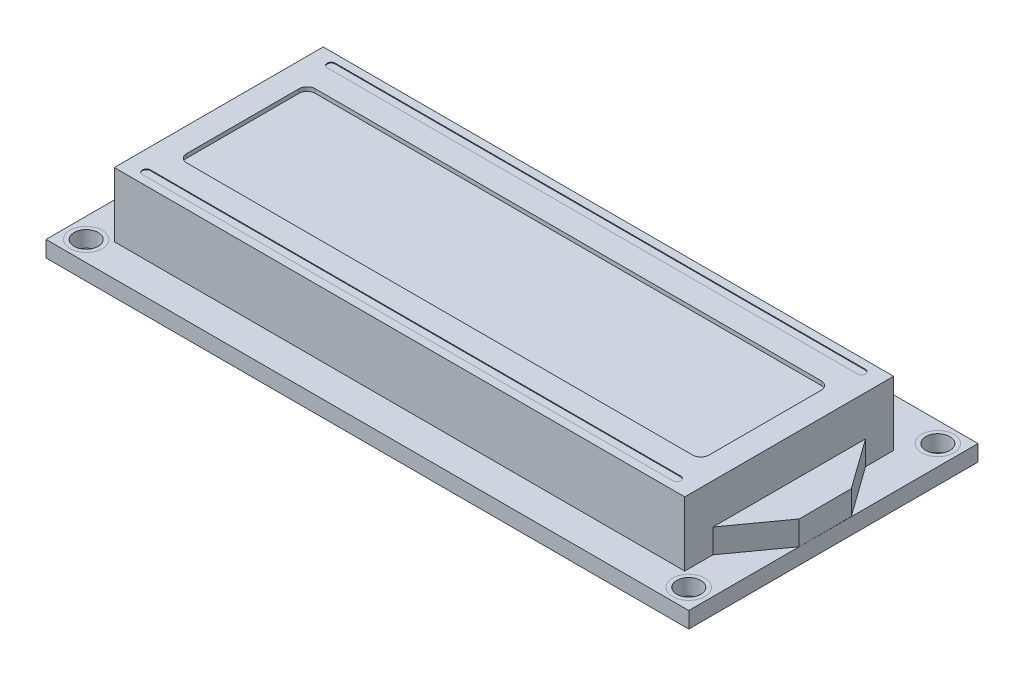
SolidWorks part; units mm, degrees
ref_plane "Front Plane" through (0, 0, 0) normal (0, 0, 1) x (1, 0, 0)
ref_plane "Top Plane" through (0, 0, 0) normal (0, 1, 0) x (1, 0, 0)
ref_plane "Right Plane" through (0, 0, 0) normal (1, 0, 0) x (0, 0, -1)
sketch "Sketch1" plane through (0, 0, 0) normal (0, 1, 0) x (1, 0, 0)
  line L1 (40, 18) -> (-40, 18)
  line L2 (40, 18) -> (40, -18)
  line L3 (40, -18) -> (-40, -18)
  line L4 (-40, 18) -> (-40, -18)
  line L5 (40, 18) -> (-40, -18) construction
  line L6 (40, -18) -> (-40, 18) construction
  point P0 (0, 0)
  dimension "D1" = 80
  dimension "D2" = 36
extrude "Boss-Extrude1" add sketch "Sketch1" along normal blind 2
sketch "Sketch2" plane through (0, 2, 0) normal (0, 1, 0) x (1, 0, 0)
  line L0 (-40, 18) -> (-40, 15.5)
  line L1 (-40, 18) -> (-40, -18) construction
  line L2 (-40, 15.5) -> (-37.5, 15.5)
  line L3 (0, 0) -> (0, 50000) construction
  line L4 (0, 0) -> (50000, 0) construction
  circle A0 centre (-37.5, 15.5) radius 1.5
  circle A1 centre (37.5, 15.5) radius 1.5
  circle A2 centre (-37.5, -15.5) radius 1.5
  circle A3 centre (37.5, -15.5) radius 1.5
  dimension "D3" = 3
  dimension "D1" = 2.5
  dimension "D2" = 2.5
extrude "Cut-Extrude1" cut sketch "Sketch2" against normal through all contours A2 | A0 | A1 | A3
sketch "Sketch3" plane through (0, 2, 0) normal (0, 1, 0) x (1, 0, 0)
  line L0 (0, -18) -> (0, -14) construction
  line L1 (-40, -18) -> (40, -18) construction
  line L2 (0, 18) -> (0, 12) construction
  line L3 (40, 18) -> (-40, 18) construction
  line L4 (-40, 0) -> (-35.5, 0) construction
  line L5 (-40, 18) -> (-40, -18) construction
  line L6 (40, 0) -> (35.5, 0) construction
  line L7 (40, -18) -> (40, 18) construction
  line L8 (-35.5, -1.0136) -> (-35.5, -50001.0136) construction
  line L9 (0, -14) -> (50000, -14) construction
  line L10 (35.5, 0) -> (35.5, -50000) construction
  line L11 (0, 12) -> (50000, 12) construction
  line L13 (-35.5, 12) -> (35.5, 12)
  line L14 (-35.5, 12) -> (-35.5, -14)
  line L15 (-35.5, -14) -> (35.5, -14)
  line L16 (35.5, 12) -> (35.5, -14)
  dimension "D1" = 4.5
  dimension "D2" = 4
  dimension "D3" = 6
extrude "Boss-Extrude2" add sketch "Sketch3" along normal blind 8 contours L14 L15 L16 L13
sketch "Sketch5" plane through (0, 10, 0) normal (0, 1, 0) x (1, 0, 0)
  line L4 (0, 12) -> (0, 7) construction
  line L5 (-35.5, 12) -> (35.5, 12) construction
  line L6 (-35.5, -1) -> (-32.5, -1) construction
  line L7 (-35.5, 12) -> (-35.5, -14) construction
  line L8 (35.5, -1) -> (32.5, -1) construction
  line L9 (35.5, 12) -> (35.5, -14) construction
  line L10 (0, -14) -> (0, -9) construction
  line L11 (-35.5, -14) -> (35.5, -14) construction
  line L12 (-32.5, -1) -> (-32.5, -50001) construction
  line L13 (0.9619, 7) -> (50000.9619, 7) construction
  line L14 (32.5, -1) -> (32.5, -50001) construction
  line L15 (0, -9) -> (50000, -9) construction
  line L17 (-31.5, 7) -> (31.5, 7)
  line L18 (-32.5, 6) -> (-32.5, -8)
  line L19 (-31.5, -9) -> (31.5, -9)
  line L20 (32.5, 6) -> (32.5, -8)
  arc A0 (31.5, -9) -> (32.5, -8) centre (31.5, -8) ccw
  arc A1 (32.5, 6) -> (31.5, 7) centre (31.5, 6) ccw
  arc A2 (-31.5, 7) -> (-32.5, 6) centre (-31.5, 6) ccw
  arc A3 (-32.5, -8) -> (-31.5, -9) centre (-31.5, -8) ccw
  point P31 (32.5, -9)
  point P36 (-32.5, 7)
  dimension "D3" = 1
  dimension "D1" = 3
  dimension "D2" = 5
extrude "Cut-Extrude2" cut sketch "Sketch5" against normal blind 0.5
sketch "Sketch6" plane through (0, 10, 0) normal (0, 1, 0) x (1, 0, 0)
  line L0 (-35.5, 12) -> (-35.5, 11) construction
  line L1 (-35.5, 12) -> (-35.5, -14) construction
  line L2 (-35.5, 11) -> (-35.5, 10) construction
  line L3 (-35.5, 12) -> (-35.5, -14) construction
  line L4 (-35.5, 10) -> (49964.5, 10) construction
  line L5 (-35.5, 11) -> (49964.5, 11) construction
  line L6 (-35.5, 12) -> (-33.5, 12) construction
  line L7 (-35.5, 12) -> (35.5, 12) construction
  line L8 (-33.5, 12) -> (-33.5, 10) construction
  line L9 (35.5, 12) -> (33.5, 12) construction
  line L10 (33.5, 12) -> (33.5, 10) construction
  line L11 (-32.5, -1) -> (49967.5, -1) construction
  line L12 (33.01, 10) -> (-33.01, 10)
  line L13 (33.5, 10.49) -> (33.5, 10.51)
  line L14 (33.01, 11) -> (-33.01, 11)
  line L15 (-33.5, 10.49) -> (-33.5, 10.51)
  line L16 (-32.5, 6) -> (-32.5, -8) construction
  line L17 (33.5, -14) -> (33.5, -12) construction
  line L18 (35.5, -14) -> (33.5, -14) construction
  line L19 (-33.5, -14) -> (-33.5, -12) construction
  line L20 (-35.5, -14) -> (-33.5, -14) construction
  line L21 (-35.5, -13) -> (49964.5, -13) construction
  line L22 (-35.5, -12) -> (49964.5, -12) construction
  line L23 (-35.5, -13) -> (-35.5, -12) construction
  line L24 (-35.5, -14) -> (-35.5, -13) construction
  line L25 (-33.5, -12.49) -> (-33.5, -12.51)
  line L26 (33.01, -13) -> (-33.01, -13)
  line L27 (33.5, -12.49) -> (33.5, -12.51)
  line L28 (33.01, -12) -> (-33.01, -12)
  arc A0 (33.5, 10.51) -> (33.01, 11) centre (33.01, 10.51) ccw
  arc A1 (33.5, 10.49) -> (33.01, 10) centre (33.01, 10.49) cw
  arc A2 (-33.5, 10.51) -> (-33.01, 11) centre (-33.01, 10.51) cw
  arc A3 (-33.5, 10.49) -> (-33.01, 10) centre (-33.01, 10.49) ccw
  arc A4 (-33.5, -12.49) -> (-33.01, -12) centre (-33.01, -12.49) cw
  arc A5 (-33.5, -12.51) -> (-33.01, -13) centre (-33.01, -12.51) ccw
  arc A6 (33.5, -12.49) -> (33.01, -12) centre (33.01, -12.49) ccw
  arc A7 (33.5, -12.51) -> (33.01, -13) centre (33.01, -12.51) cw
  point P29 (-33.5, 11)
  point P37 (-32.5, -1)
  point P62 (-33.5, -13)
  dimension "D5" = 0.49
  dimension "D1" = 1
  dimension "D2" = 1
  dimension "D3" = 2
  dimension "D4" = 2
extrude "Cut-Extrude3" cut sketch "Sketch6" against normal blind 0.1
sketch "Sketch7" plane through (0, 2, 0) normal (0, 1, 0) x (1, 0, 0)
  line L0 (35.5, 8.5) -> (35.5, -10.5)
  line L1 (35.5, 12) -> (35.5, -14) construction
  line L3 (35.5, -1) -> (39.99, -1) construction
  line L4 (39.98, 2.25) -> (40, -4.25)
  line L5 (40, -18) -> (40, 18) construction
  line L6 (35.5, 8.5) -> (39.98, 2.25)
  line L7 (40, -4.25) -> (35.5, -10.5)
  point P5 (35.5, -1)
  point P12 (39.99, -1)
  dimension "D1" = 19
  dimension "D2" = 4.49
  dimension "D3" = 6.5
extrude "Boss-Extrude3" add sketch "Sketch7" along normal blind 3
sketch "Sketch8" plane through (0, 2, 0) normal (0, 1, 0) x (1, 0, 0)
  line L0 (0, 0) -> (-50000, 0) construction
  line L1 (0, 0) -> (0, 50000) construction
  line L2 (-40, 18) -> (-33, 18) construction
  line L3 (40, 18) -> (-40, 18) construction
  line L4 (-32, 18) -> (-32, 16) construction
  line L5 (-33, 18) -> (-31, 18)
  line L6 (-33, 18) -> (-33, 16)
  line L7 (-30.5, 18) -> (-28.5, 18)
  line L8 (-31, 18) -> (-31, 16)
  line L9 (-32, 15) -> (-32, 16) construction
  line L10 (-30.5, 18) -> (-30.5, 16)
  line L11 (-28.5, 18) -> (-28.5, 16)
  line L12 (-29.5, 18) -> (-29.5, 16) construction
  line L13 (-29.5, 15) -> (-29.5, 16) construction
  line L14 (-28, 18) -> (-26, 18)
  line L15 (-28, 18) -> (-28, 16)
  line L16 (-26, 18) -> (-26, 16)
  line L17 (-27, 18) -> (-27, 16) construction
  line L18 (-27, 15) -> (-27, 16) construction
  line L19 (-25.5, 18) -> (-23.5, 18)
  line L20 (-25.5, 18) -> (-25.5, 16)
  line L21 (-23.5, 18) -> (-23.5, 16)
  line L22 (-24.5, 18) -> (-24.5, 16) construction
  line L23 (-24.5, 15) -> (-24.5, 16) construction
  line L24 (-23, 18) -> (-21, 18)
  line L25 (-23, 18) -> (-23, 16)
  line L26 (-21, 18) -> (-21, 16)
  line L27 (-22, 18) -> (-22, 16) construction
  line L28 (-22, 15) -> (-22, 16) construction
  line L29 (-20.5, 18) -> (-18.5, 18)
  line L30 (-20.5, 18) -> (-20.5, 16)
  line L31 (-18.5, 18) -> (-18.5, 16)
  line L32 (-19.5, 18) -> (-19.5, 16) construction
  line L33 (-19.5, 15) -> (-19.5, 16) construction
  line L34 (-18, 18) -> (-16, 18)
  line L35 (-18, 18) -> (-18, 16)
  line L36 (-16, 18) -> (-16, 16)
  line L37 (-17, 18) -> (-17, 16) construction
  line L38 (-17, 15) -> (-17, 16) construction
  line L39 (-15.5, 18) -> (-13.5, 18)
  line L40 (-15.5, 18) -> (-15.5, 16)
  line L41 (-13.5, 18) -> (-13.5, 16)
  line L42 (-14.5, 18) -> (-14.5, 16) construction
  line L43 (-14.5, 15) -> (-14.5, 16) construction
  line L44 (-13, 18) -> (-11, 18)
  line L45 (-13, 18) -> (-13, 16)
  line L46 (-11, 18) -> (-11, 16)
  line L47 (-12, 18) -> (-12, 16) construction
  line L48 (-12, 15) -> (-12, 16) construction
  line L49 (-10.5, 18) -> (-8.5, 18)
  line L50 (-10.5, 18) -> (-10.5, 16)
  line L51 (-8.5, 18) -> (-8.5, 16)
  line L52 (-9.5, 18) -> (-9.5, 16) construction
  line L53 (-9.5, 15) -> (-9.5, 16) construction
  line L54 (-8, 18) -> (-6, 18)
  line L55 (-8, 18) -> (-8, 16)
  line L56 (-6, 18) -> (-6, 16)
  line L57 (-7, 18) -> (-7, 16) construction
  line L58 (-7, 15) -> (-7, 16) construction
  line L59 (-5.5, 18) -> (-3.5, 18)
  line L60 (-5.5, 18) -> (-5.5, 16)
  line L61 (-3.5, 18) -> (-3.5, 16)
  line L62 (-4.5, 18) -> (-4.5, 16) construction
  line L63 (-4.5, 15) -> (-4.5, 16) construction
  line L64 (-3, 18) -> (-1, 18)
  line L65 (-3, 18) -> (-3, 16)
  line L66 (-1, 18) -> (-1, 16)
  line L67 (-2, 18) -> (-2, 16) construction
  line L68 (-2, 15) -> (-2, 16) construction
  line L69 (-0.5, 18) -> (1.5, 18)
  line L70 (-0.5, 18) -> (-0.5, 16)
  line L71 (1.5, 18) -> (1.5, 16)
  line L72 (0.5, 18) -> (0.5, 16) construction
  line L73 (0.5, 15) -> (0.5, 16) construction
  line L74 (2, 18) -> (4, 18)
  line L75 (2, 18) -> (2, 16)
  line L76 (4, 18) -> (4, 16)
  line L77 (3, 18) -> (3, 16) construction
  line L78 (3, 15) -> (3, 16) construction
  line L79 (4.5, 18) -> (6.5, 18)
  line L80 (4.5, 18) -> (4.5, 16)
  line L81 (6.5, 18) -> (6.5, 16)
  line L82 (5.5, 18) -> (5.5, 16) construction
  line L83 (5.5, 15) -> (5.5, 16) construction
  circle A0 centre (-37.5, 15.5) radius 2
  circle A1 centre (37.5, 15.5) radius 2
  circle A2 centre (37.5, -15.5) radius 2
  circle A3 centre (-37.5, -15.5) radius 2
  arc A4 (-33, 16) -> (-31, 16) centre (-32, 16) ccw
  arc A5 (-30.5, 16) -> (-28.5, 16) centre (-29.5, 16) ccw
  arc A6 (-28, 16) -> (-26, 16) centre (-27, 16) ccw
  arc A7 (-25.5, 16) -> (-23.5, 16) centre (-24.5, 16) ccw
  arc A8 (-23, 16) -> (-21, 16) centre (-22, 16) ccw
  arc A9 (-20.5, 16) -> (-18.5, 16) centre (-19.5, 16) ccw
  arc A10 (-18, 16) -> (-16, 16) centre (-17, 16) ccw
  arc A11 (-15.5, 16) -> (-13.5, 16) centre (-14.5, 16) ccw
  arc A12 (-13, 16) -> (-11, 16) centre (-12, 16) ccw
  arc A13 (-10.5, 16) -> (-8.5, 16) centre (-9.5, 16) ccw
  arc A14 (-8, 16) -> (-6, 16) centre (-7, 16) ccw
  arc A15 (-5.5, 16) -> (-3.5, 16) centre (-4.5, 16) ccw
  arc A16 (-3, 16) -> (-1, 16) centre (-2, 16) ccw
  arc A17 (-0.5, 16) -> (1.5, 16) centre (0.5, 16) ccw
  arc A18 (2, 16) -> (4, 16) centre (3, 16) ccw
  arc A19 (4.5, 16) -> (6.5, 16) centre (5.5, 16) ccw
  dimension "D1" = 4
  dimension "D2" = 7
  dimension "D3" = 16
split line "Split Line1"
sketch "Sketch10" plane through (0, 2, 0) normal (0, 1, 0) x (1, 0, 0)
  circle A0 centre (-32, 16) radius 0.5
  circle A1 centre (-29.5, 16) radius 0.5
  circle A2 centre (-27, 16) radius 0.5
  circle A3 centre (-24.5, 16) radius 0.5
  circle A4 centre (-22, 16) radius 0.5
  circle A5 centre (-19.5, 16) radius 0.5
  circle A6 centre (-17, 16) radius 0.5
  circle A7 centre (-14.5, 16) radius 0.5
  circle A8 centre (-12, 16) radius 0.5
  circle A9 centre (-9.5, 16) radius 0.5
  circle A10 centre (-7, 16) radius 0.5
  circle A11 centre (-4.5, 16) radius 0.5
  circle A12 centre (-2, 16) radius 0.5
  circle A13 centre (0.5, 16) radius 0.5
  circle A14 centre (3, 16) radius 0.5
  circle A15 centre (5.5, 16) radius 0.5
  dimension "D1" = 1
  dimension "D2" = 16
extrude "Cut-Extrude4" cut sketch "Sketch10" against normal through all
sketch "Sketch14" plane through (0, 0, 0) normal (0, 1, 0) x (1, 0, 0)
  line L0 (0, 0) -> (-50000, 0) construction
  line L1 (0, 0) -> (0, 50000) construction
  line L2 (-40, 18) -> (-33, 18) construction
  line L4 (-32, 18) -> (-32, 16) construction
  line L5 (-33, 18) -> (-31, 18)
  line L6 (-33, 18) -> (-33, 16)
  line L7 (-30.5, 18) -> (-28.5, 18)
  line L8 (-31, 18) -> (-31, 16)
  line L9 (-32, 15) -> (-32, 16) construction
  line L10 (-30.5, 18) -> (-30.5, 16)
  line L11 (-28.5, 18) -> (-28.5, 16)
  line L12 (-29.5, 18) -> (-29.5, 16) construction
  line L13 (-29.5, 15) -> (-29.5, 16) construction
  line L14 (-28, 18) -> (-26, 18)
  line L15 (-28, 18) -> (-28, 16)
  line L16 (-26, 18) -> (-26, 16)
  line L17 (-27, 18) -> (-27, 16) construction
  line L18 (-27, 15) -> (-27, 16) construction
  line L19 (-25.5, 18) -> (-23.5, 18)
  line L20 (-25.5, 18) -> (-25.5, 16)
  line L21 (-23.5, 18) -> (-23.5, 16)
  line L22 (-24.5, 18) -> (-24.5, 16) construction
  line L23 (-24.5, 15) -> (-24.5, 16) construction
  line L24 (-23, 18) -> (-21, 18)
  line L25 (-23, 18) -> (-23, 16)
  line L26 (-21, 18) -> (-21, 16)
  line L27 (-22, 18) -> (-22, 16) construction
  line L28 (-22, 15) -> (-22, 16) construction
  line L29 (-20.5, 18) -> (-18.5, 18)
  line L30 (-20.5, 18) -> (-20.5, 16)
  line L31 (-18.5, 18) -> (-18.5, 16)
  line L32 (-19.5, 18) -> (-19.5, 16) construction
  line L33 (-19.5, 15) -> (-19.5, 16) construction
  line L34 (-18, 18) -> (-16, 18)
  line L35 (-18, 18) -> (-18, 16)
  line L36 (-16, 18) -> (-16, 16)
  line L37 (-17, 18) -> (-17, 16) construction
  line L38 (-17, 15) -> (-17, 16) construction
  line L39 (-15.5, 18) -> (-13.5, 18)
  line L40 (-15.5, 18) -> (-15.5, 16)
  line L41 (-13.5, 18) -> (-13.5, 16)
  line L42 (-14.5, 18) -> (-14.5, 16) construction
  line L43 (-14.5, 15) -> (-14.5, 16) construction
  line L44 (-13, 18) -> (-11, 18)
  line L45 (-13, 18) -> (-13, 16)
  line L46 (-11, 18) -> (-11, 16)
  line L47 (-12, 18) -> (-12, 16) construction
  line L48 (-12, 15) -> (-12, 16) construction
  line L49 (-10.5, 18) -> (-8.5, 18)
  line L50 (-10.5, 18) -> (-10.5, 16)
  line L51 (-8.5, 18) -> (-8.5, 16)
  line L52 (-9.5, 18) -> (-9.5, 16) construction
  line L53 (-9.5, 15) -> (-9.5, 16) construction
  line L54 (-8, 18) -> (-6, 18)
  line L55 (-8, 18) -> (-8, 16)
  line L56 (-6, 18) -> (-6, 16)
  line L57 (-7, 18) -> (-7, 16) construction
  line L58 (-7, 15) -> (-7, 16) construction
  line L59 (-5.5, 18) -> (-3.5, 18)
  line L60 (-5.5, 18) -> (-5.5, 16)
  line L61 (-3.5, 18) -> (-3.5, 16)
  line L62 (-4.5, 18) -> (-4.5, 16) construction
  line L63 (-4.5, 15) -> (-4.5, 16) construction
  line L64 (-3, 18) -> (-1, 18)
  line L65 (-3, 18) -> (-3, 16)
  line L66 (-1, 18) -> (-1, 16)
  line L67 (-2, 18) -> (-2, 16) construction
  line L68 (-2, 15) -> (-2, 16) construction
  line L69 (-0.5, 18) -> (1.5, 18)
  line L70 (-0.5, 18) -> (-0.5, 16)
  line L71 (1.5, 18) -> (1.5, 16)
  line L72 (0.5, 18) -> (0.5, 16) construction
  line L73 (0.5, 15) -> (0.5, 16) construction
  line L74 (2, 18) -> (4, 18)
  line L75 (2, 18) -> (2, 16)
  line L76 (4, 18) -> (4, 16)
  line L77 (3, 18) -> (3, 16) construction
  line L78 (3, 15) -> (3, 16) construction
  line L79 (4.5, 18) -> (6.5, 18)
  line L80 (4.5, 18) -> (4.5, 16)
  line L81 (6.5, 18) -> (6.5, 16)
  line L82 (5.5, 18) -> (5.5, 16) construction
  line L83 (5.5, 15) -> (5.5, 16) construction
  circle A0 centre (-37.5, 15.5) radius 2
  circle A1 centre (37.5, 15.5) radius 2
  circle A2 centre (37.5, -15.5) radius 2
  circle A3 centre (-37.5, -15.5) radius 2
  arc A4 (-33, 16) -> (-31, 16) centre (-32, 16) ccw
  arc A5 (-30.5, 16) -> (-28.5, 16) centre (-29.5, 16) ccw
  arc A6 (-28, 16) -> (-26, 16) centre (-27, 16) ccw
  arc A7 (-25.5, 16) -> (-23.5, 16) centre (-24.5, 16) ccw
  arc A8 (-23, 16) -> (-21, 16) centre (-22, 16) ccw
  arc A9 (-20.5, 16) -> (-18.5, 16) centre (-19.5, 16) ccw
  arc A10 (-18, 16) -> (-16, 16) centre (-17, 16) ccw
  arc A11 (-15.5, 16) -> (-13.5, 16) centre (-14.5, 16) ccw
  arc A12 (-13, 16) -> (-11, 16) centre (-12, 16) ccw
  arc A13 (-10.5, 16) -> (-8.5, 16) centre (-9.5, 16) ccw
  arc A14 (-8, 16) -> (-6, 16) centre (-7, 16) ccw
  arc A15 (-5.5, 16) -> (-3.5, 16) centre (-4.5, 16) ccw
  arc A16 (-3, 16) -> (-1, 16) centre (-2, 16) ccw
  arc A17 (-0.5, 16) -> (1.5, 16) centre (0.5, 16) ccw
  arc A18 (2, 16) -> (4, 16) centre (3, 16) ccw
  arc A19 (4.5, 16) -> (6.5, 16) centre (5.5, 16) ccw
  dimension "D1" = 4
  dimension "D2" = 7
  dimension "D3" = 16
split line "Split Line2"
